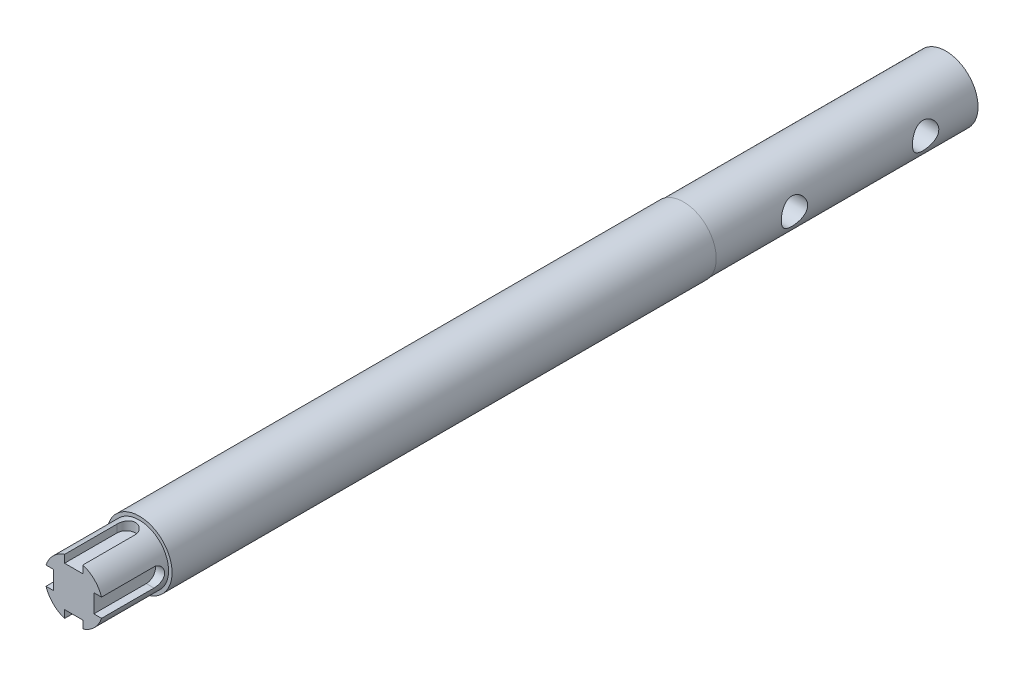
SolidWorks part; units mm, degrees
material "AISI 304"
ref_plane "Front Plane" through (0, 0, 0) normal (0, 0, 1) x (1, 0, 0)
ref_plane "Top Plane" through (0, 0, 0) normal (0, 1, 0) x (1, 0, 0)
ref_plane "Right Plane" through (0, 0, 0) normal (1, 0, 0) x (0, 0, -1)
sketch "Sketch1" plane through (0, 0, 0) normal (0, 0, 1) x (1, 0, 0)
  circle A0 centre (0, 0) radius 24.95
  dimension "D1" = 49.9
extrude "Boss-Extrude1" add sketch "Sketch1" along normal mid plane 665
sketch "Sketch2" plane through (0, 0, 0) normal (1, 0, 0) x (0, 0, -1)
  line L0 (-332.5, 0) -> (0, 0) construction
  line L1 (-332.5, 24.95) -> (-332.5, -24.95) construction
  line L2 (332.5, -24.95) -> (332.5, 24.95) construction
  circle A0 centre (192.5, 0) radius 10.05
  circle A1 centre (292.5, 0) radius 10.05
  dimension "D1" = 20.1
  dimension "D3" = 100
  dimension "D2" = 40
extrude "Cut-Extrude1" cut sketch "Sketch2" against normal through all both and the other way through all
ref_plane "Plane1" through (-18.5, 0, 0) normal (1, 0, 0) x (0, 0, -1)
sketch "Sketch3" plane through (-18.5, 0, 0) normal (1, 0, 0) x (0, 0, -1)
  line L0 (-332.5, 0) -> (-27.9799, 0) construction
  line L1 (-332.5, 24.95) -> (-332.5, -24.95) construction
  line L2 (332.5, -24.95) -> (332.5, 24.95) construction
  line L3 (-212.5, -7) -> (-170.5, -7)
  line L5 (-212.5, 7) -> (-170.5, 7)
  arc A0 (-212.5, 7) -> (-212.5, -7) centre (-212.5, 0) ccw
  arc A1 (-170.5, -7) -> (-170.5, 7) centre (-170.5, 0) ccw
  dimension "D2" = 7
  dimension "D1" = 42
  dimension "D3" = 503
extrude "Cut-Extrude2" cut sketch "Sketch3" against normal through all
pattern_linear "LPattern1" [suppressed] count 2 spacing 400
sketch "Sketch5" plane through (0, 0, -332.5) normal (0, 0, -1) x (-1, 0, 0)
  circle A0 centre (0, 0) radius 24.61
  dimension "D1" = 49.22
extrude "Cut-Extrude4" cut sketch "Sketch5" against normal blind 200 flip side to cut
sketch "Sketch7" plane through (0, 0, 332.5) normal (0, 0, 1) x (1, 0, 0)
  circle A0 centre (0, 0) radius 22.3
  dimension "D1" = 44.6
extrude "Cut-Extrude6" cut sketch "Sketch7" against normal blind 50 flip side to cut
ref_plane "Plane2" through (3.8724, 21.9612, 0) normal (0.1736, 0.9848, 0) x (0, 0, 1)
sketch "Sketch9" plane through (-18.5, 0, 0) normal (-1, 0, 0) x (0, 0, 1)
  line L0 (292.5, 0) -> (332.5, 0) construction
  line L1 (292.5, 7) -> (332.5, 7)
  line L2 (292.5, -7) -> (332.5, -7)
  line L3 (282.5, -24.95) -> (282.5, 24.95) construction
  arc A0 (292.5, 7) -> (292.5, -7) centre (292.5, 0) ccw
  arc A1 (332.5, -7) -> (332.5, 7) centre (332.5, 0) ccw
  point P3 (312.5, 0)
  dimension "D2" = 7
  dimension "D1" = 40
  dimension "D3" = 10
extrude "Cut-Extrude8" cut sketch "Sketch9" along normal blind 10 and the other way blind 3.2 contours L1 A1 L2 A0
pattern_circular "CirPattern1" count 4 over 360 about axis through (0, 0, 0) along (0, 0, 1) of "Cut-Extrude8"
